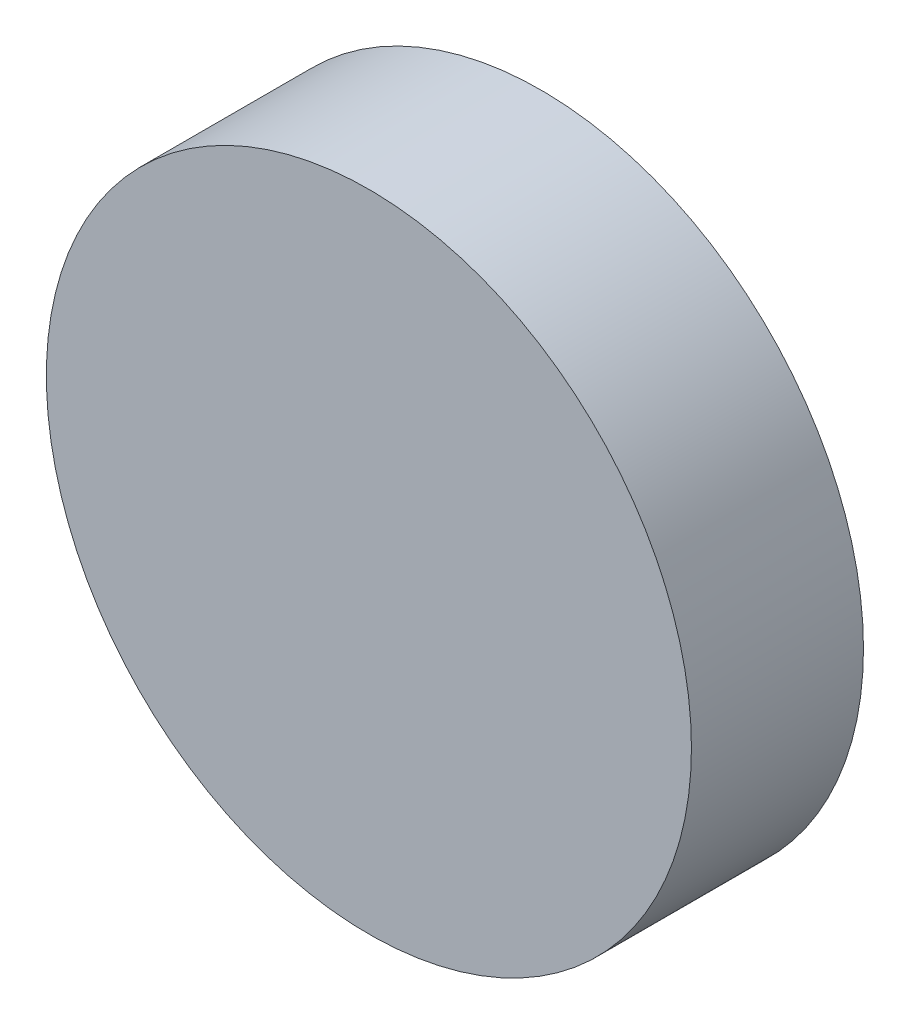
SolidWorks part; units mm, degrees
ref_plane "Front Plane" through (0, 0, 0) normal (0, 0, 1) x (1, 0, 0)
ref_plane "Top Plane" through (0, 0, 0) normal (0, 1, 0) x (1, 0, 0)
ref_plane "Right Plane" through (0, 0, 0) normal (1, 0, 0) x (0, 0, -1)
sketch "Sketch2" plane through (0, 0, 0) normal (0, 0, 1) x (1, 0, 0)
  circle A0 centre (0, 0) radius 15
  dimension "D1" = 30
extrude "Boss-Extrude1" add sketch "Sketch2" along normal blind 8
sketch "Sketch3" plane through (0, 0, 0) normal (0, 0, -1) x (-1, 0, 0)
  circle A0 centre (0, 0) radius 3
extrude "Cut-Extrude1" cut sketch "Sketch3" against normal offset from surface (7.8 mm away) 0.2 up to face at (15, 0, 8)
